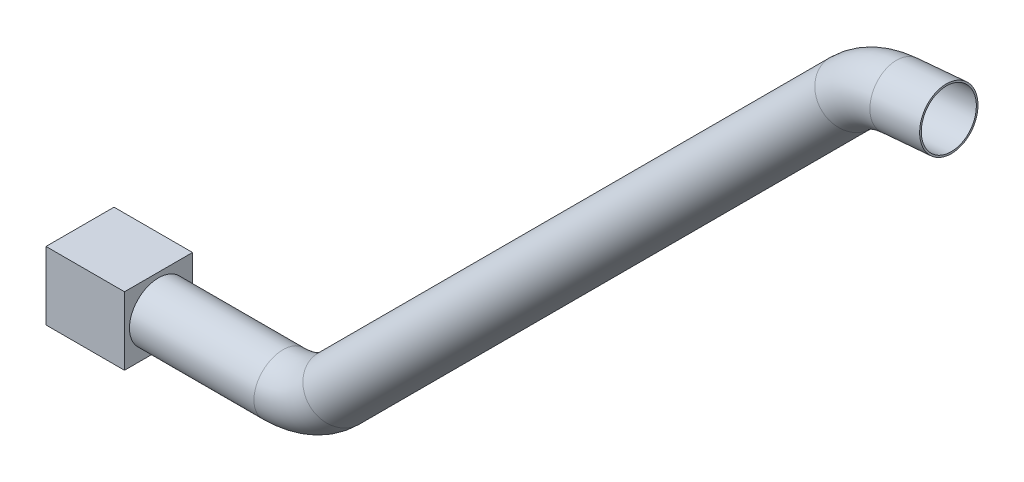
SolidWorks part; units mm, degrees
ref_plane "Front" through (0, 0, 0) normal (0, 0, 1) x (1, 0, 0)
ref_plane "Top" through (0, 0, 0) normal (0, 1, 0) x (1, 0, 0)
ref_plane "Right" through (0, 0, 0) normal (1, 0, 0) x (0, 0, -1)
sketch "Croquis1" plane through (0, 0, 0) normal (0, 0, 1) x (1, 0, 0)
  line L0 (0, 0) -> (237.868, 0)
  line L1 (343.934, 43.934) -> (1322.0553, 1022.0553)
  line L2 (1415.048, 1065.4185) -> (1510.0894, 1073.7335)
  line L3 (1415.048, 1065.4185) -> (1538.1061, 1065.4185) construction
  arc A0 (237.868, 0) -> (343.934, 43.934) centre (237.868, 150) ccw
  arc A1 (1322.0553, 1022.0553) -> (1415.048, 1065.4185) centre (1428.1213, 915.9893) cw
  point P7 (300, 0)
  point P10 (1360.6602, 1060.6602)
  dimension "D5" = 150
  dimension "D1" = 45
  dimension "D2" = 1500
  dimension "D3" = 300
  dimension "D4" = 150
  dimension "D6" = 5
sweep "Barrer2" add path "Croquis1" circular profile diameter 111.125 parameters "D3"=111.125
shell "Vaciado1" thickness 3.175
sketch "Croquis2" plane through (0, 0, 0) normal (-1, 0, 0) x (0, 0, 1)
  line L1 (-65, 65) -> (65, 65)
  line L2 (-65, 65) -> (-65, -65)
  line L3 (-65, -65) -> (65, -65)
  line L4 (65, 65) -> (65, -65)
  line L5 (-65, 65) -> (65, -65) construction
  line L6 (-65, -65) -> (65, 65) construction
  point P0 (0, 0)
  dimension "D1" = 130
  dimension "D2" = 130
extrude "Saliente-Extruir1" add sketch "Croquis2" along normal blind 150
equation "\"Largo\"= 1500mm"
equation "\"D2@Croquis1\"=\"Largo\""
